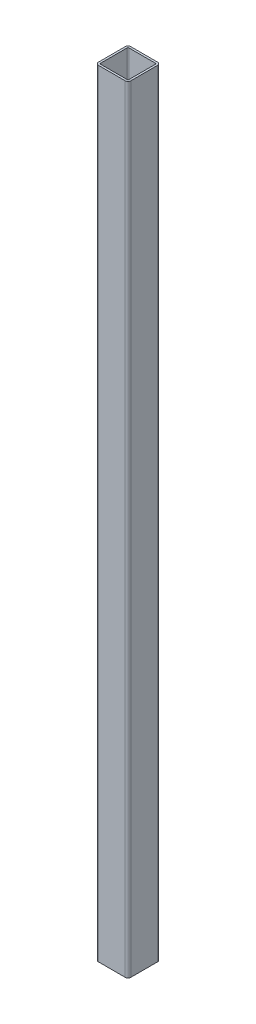
SolidWorks part; units mm, degrees
material "AISI 1015 Steel, Cold Drawn (SS)"
ref_plane "Front Plane" through (0, 0, 0) normal (0, 0, 1) x (1, 0, 0)
ref_plane "Top Plane" through (0, 0, 0) normal (0, 1, 0) x (1, 0, 0)
ref_plane "Right Plane" through (0, 0, 0) normal (1, 0, 0) x (0, 0, -1)
sketch "Sketch2" plane through (0, 0, 0) normal (0, 1, 0) x (1, 0, 0)
  line L0 (-20.955, -22.225) -> (20.955, -22.225)
  line L1 (-20.955, -25.4) -> (20.955, -25.4)
  line L2 (-25.4, -20.955) -> (-25.4, 20.955)
  line L3 (-20.955, 25.4) -> (20.955, 25.4)
  line L4 (25.4, -20.955) -> (25.4, 20.955)
  line L5 (-25.4, -25.4) -> (25.4, 25.4) construction
  line L6 (-25.4, 25.4) -> (25.4, -25.4) construction
  line L7 (22.225, -20.955) -> (22.225, 20.955)
  line L8 (-20.955, 22.225) -> (20.955, 22.225)
  line L9 (-22.225, -20.955) -> (-22.225, 20.955)
  arc A0 (20.955, 25.4) -> (25.4, 20.955) centre (20.955, 20.955) cw
  arc A1 (20.955, -25.4) -> (25.4, -20.955) centre (20.955, -20.955) ccw
  arc A2 (-20.955, -25.4) -> (-25.4, -20.955) centre (-20.955, -20.955) cw
  arc A3 (-25.4, 20.955) -> (-20.955, 25.4) centre (-20.955, 20.955) cw
  arc A4 (20.955, -22.225) -> (22.225, -20.955) centre (20.955, -20.955) ccw
  arc A5 (20.955, 22.225) -> (22.225, 20.955) centre (20.955, 20.955) cw
  arc A6 (-22.225, 20.955) -> (-20.955, 22.225) centre (-20.955, 20.955) cw
  arc A7 (-20.955, -22.225) -> (-22.225, -20.955) centre (-20.955, -20.955) cw
  point P0 (0, 0)
  point P6 (0, 0)
  dimension "D3" = 1.27
  dimension "D1" = 50.8
  dimension "D2" = 50.8
  dimension "D4" = 3.175
extrude "Boss-Extrude1" add sketch "Sketch2" along normal blind 1219.2
equation "\"D4@Sketch2\"=\"Wall Thickness\""
equation "\"D1@Boss-Extrude1\"=\"Length\""
